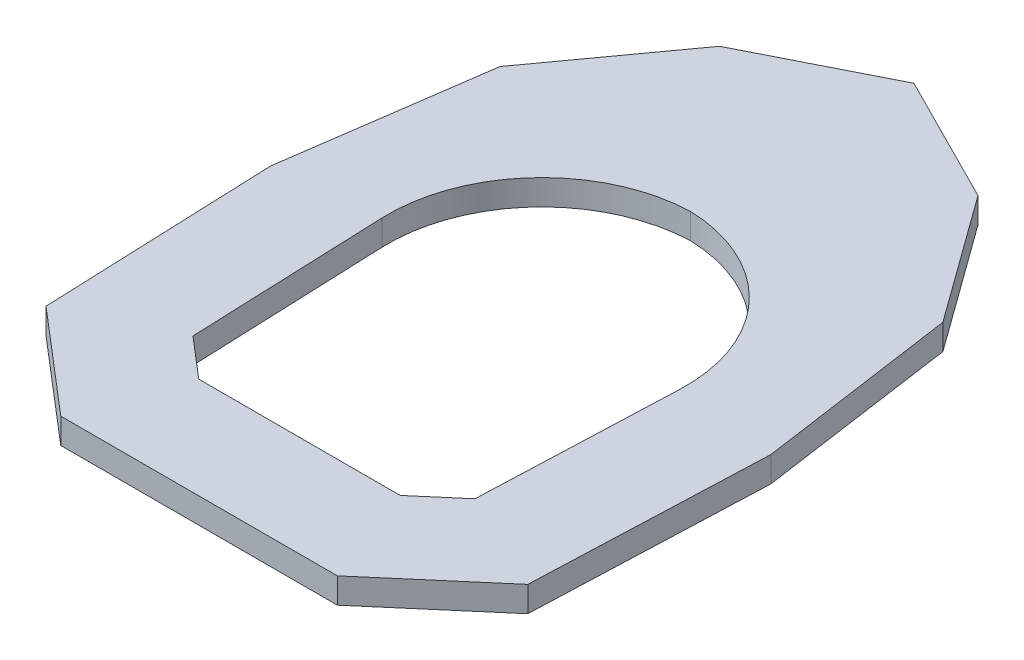
SolidWorks part; units mm, degrees
ref_plane "Front Plane" through (0, 0, 0) normal (0, 0, 1) x (1, 0, 0)
ref_plane "Top Plane" through (0, 0, 0) normal (0, 1, 0) x (1, 0, 0)
ref_plane "Right Plane" through (0, 0, 0) normal (1, 0, 0) x (0, 0, -1)
sketch "Sketch1" plane through (0, 0, 0) normal (0, 1, 0) x (1, 0, 0)
  line L6 (198.0479, -498.1678) -> (-198.0479, -498.1678)
  line L7 (-198.0479, -498.1678) -> (-277.3266, -430.3121)
  line L8 (-277.3266, -430.3121) -> (-292.424, -43.2015)
  line L18 (277.3266, -430.3121) -> (292.424, -43.2015)
  line L19 (198.0479, -498.1678) -> (277.3266, -430.3121)
  line L20 (-490.4158, -64.1941) -> (-472.4779, -524.1388)
  line L21 (-472.4779, -524.1388) -> (-270.661, -696.8767)
  line L22 (-270.661, -696.8767) -> (273.2432, -696.8767)
  line L23 (475.0601, -524.1388) -> (273.2432, -696.8767)
  line L24 (492.9981, -64.1941) -> (475.0601, -524.1388)
  line L25 (436.8035, 330.5116) -> (492.9981, -64.1941)
  line L26 (255.5269, 580.8273) -> (436.8035, 330.5116)
  line L27 (1.2911, 709.0589) -> (255.5269, 580.8273)
  line L28 (1.2911, 709.0589) -> (-252.9446, 580.8273)
  line L29 (-252.9446, 580.8273) -> (-434.2212, 330.5116)
  line L30 (-434.2212, 330.5116) -> (-490.4158, -64.1941)
  arc A0 (0, 271.0589) -> (-292.424, -43.2015) centre (9.9773, -31.4077) ccw
  arc A1 (0, 271.0589) -> (292.424, -43.2015) centre (-9.9773, -31.4077) cw
extrude "Boss-Extrude1" add sketch "Sketch1" against normal blind 50
